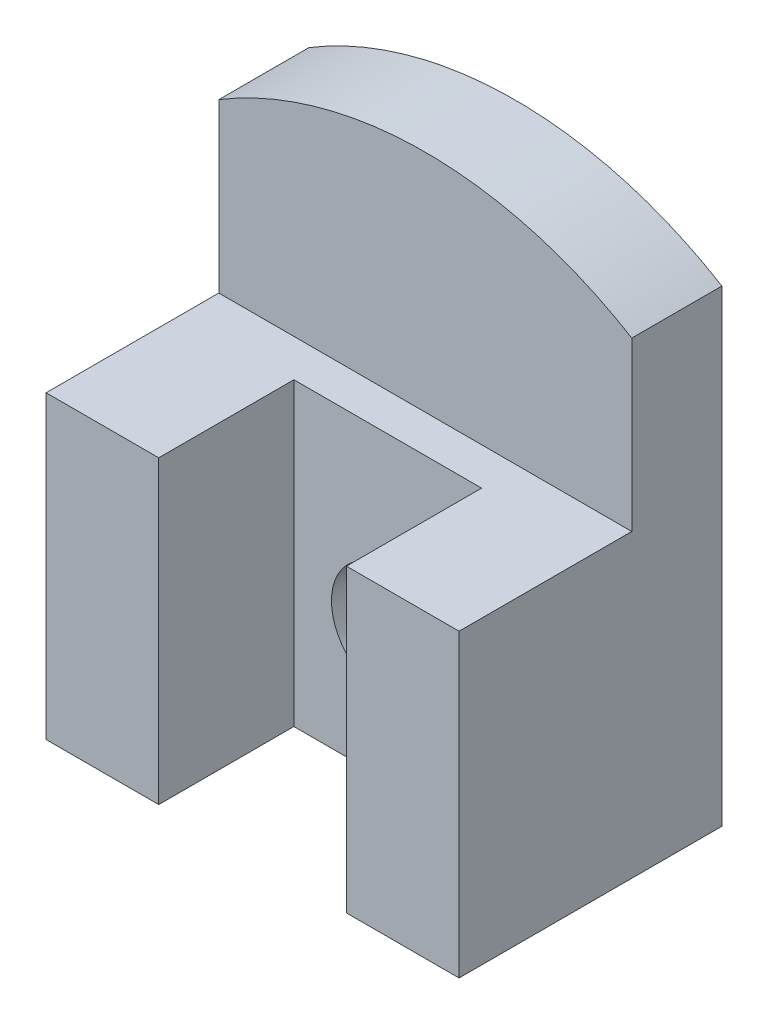
SolidWorks part; units mm, degrees
ref_plane "Plan de face" through (0, 0, 0) normal (0, 0, 1) x (1, 0, 0)
ref_plane "Plan de dessus" through (0, 0, 0) normal (0, 1, 0) x (1, 0, 0)
ref_plane "Plan de droite" through (0, 0, 0) normal (1, 0, 0) x (0, 0, -1)
sketch "Esquisse1" plane through (0, 0, 0) normal (0, 1, 0) x (1, 0, 0)
  line L0 (0, 0) -> (0, 23)
  line L1 (0, 23) -> (55, 23)
  line L2 (55, 23) -> (55, 0)
  line L3 (55, 0) -> (40, 0)
  line L4 (40, 0) -> (40, 18)
  line L5 (40, 18) -> (15, 18)
  line L6 (15, 18) -> (15, 0)
  line L7 (15, 0) -> (0, 0)
  point P9 (0, 0)
  point P10 (55, 23.2586)
  point P11 (0, 0)
  point P12 (0, 53.0816)
  point P13 (55, 23)
  point P15 (0, 0)
  point P16 (40, 18.4359)
  point P17 (53.3976, 35)
  point P18 (0, 0)
  point P19 (55, 35)
  dimension "D2" = 15
  dimension "D3" = 25
  dimension "D4" = 23
  dimension "D5" = 18
extrude "Boss.-Extru.2" add sketch "Esquisse1" along normal blind 40
sketch "Esquisse2" plane through (0, 0, 0) normal (0, 1, 0) x (1, 0, 0)
  line L1 (0, 35) -> (55, 35)
  line L2 (0, 35) -> (0, 23)
  line L3 (0, 23) -> (55, 23)
  line L4 (55, 35) -> (55, 23)
  line L5 (0, 35) -> (55, 23) construction
  line L6 (0, 23) -> (55, 35) construction
  point P0 (27.5, 29)
  point P6 (4.7166, 35)
  point P7 (0, 0)
  point P8 (0, 0)
  dimension "D1" = 12
extrude "Boss.-Extru.3" add sketch "Esquisse2" along normal blind 40
sketch "Esquisse3" plane through (0, 0, -35) normal (0, 0, -1) x (-1, 0, 0)
  line L0 (-55, 40) -> (-55, 62.3073)
  line L1 (-55, 40) -> (0, 40)
  line L2 (0, 40) -> (0, 62.3073)
  line L4 (-55, 40) -> (-55, 0) construction
  arc A0 (0, 62.3073) -> (-55, 62.3073) centre (-27.5, 17) ccw
  point P8 (-55, 62.6958)
  point P9 (0, 0)
  point P10 (-24.6126, 17.1079)
  point P11 (-27.5, 70)
  point P15 (0, 62.3073)
  dimension "D2" = 53
  dimension "D1" = 70
  dimension "D3" = 27.5
extrude "Boss.-Extru.4" add sketch "Esquisse3" against normal blind 12
sketch "Esquisse4" plane through (0, 0, -35) normal (0, 0, -1) x (-1, 0, 0)
  line L0 (-55, 0) -> (0, 0) construction
  line L1 (0, 62.3073) -> (0, 0) construction
  circle A0 centre (-27.5, 17) radius 7.5
  dimension "D2" = 15
  dimension "D1" = 17
  dimension "D3" = 27.5
extrude "Enlèv. mat.-Extru.1" cut sketch "Esquisse4" against normal through all
